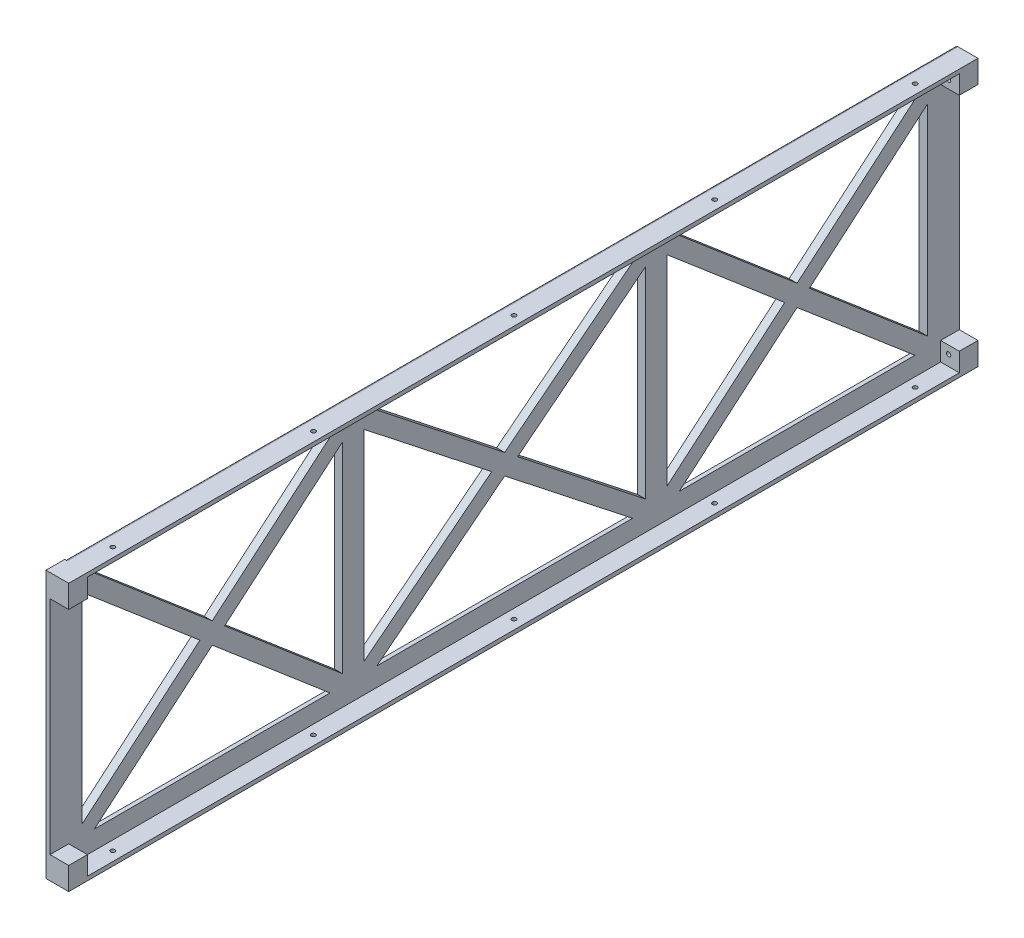
SolidWorks part; units mm, degrees
material "7075-T6 (SN)"
ref_plane "Front Plane" through (0, 0, 0) normal (0, 0, 1) x (1, 0, 0)
ref_plane "Top Plane" through (0, 0, 0) normal (0, 1, 0) x (1, 0, 0)
ref_plane "Right Plane" through (0, 0, 0) normal (1, 0, 0) x (0, 0, -1)
sketch "Sketch1" plane through (0, 0, 0) normal (0, 0, 1) x (1, 0, 0)
  line L0 (0, 0) -> (0, 100)
  line L1 (0, 100) -> (8.5, 100)
  line L2 (8.5, 100) -> (8.5, 98.5)
  line L3 (8.5, 98.5) -> (1.5, 98.5)
  line L4 (1.5, 98.5) -> (1.5, 1.5)
  line L5 (1.5, 1.5) -> (8.5, 1.5)
  line L6 (8.5, 1.5) -> (8.5, 0)
  line L7 (8.5, 0) -> (0, 0)
  dimension "D1" = 100
  dimension "D2" = 8.5
  dimension "D3" = 1.5
  dimension "D4" = 1.5
  dimension "D5" = 1.5
extrude "Profile" add sketch "Sketch1" along normal blind 340.5
ref_plane "Mid" through (0, 0, 170.25) normal (0, 0, 1) x (1, 0, 0)
sketch "Sketch2" plane through (0, 0, 0) normal (0, 0, 1) x (1, 0, 0)
  line L1 (0, 0) -> (8.5, 0)
  line L2 (0, 0) -> (0, 8.5)
  line L3 (0, 8.5) -> (8.5, 8.5)
  line L4 (8.5, 0) -> (8.5, 8.5)
  line L5 (0, 100) -> (8.5, 100)
  line L6 (0, 100) -> (0, 91.5)
  line L7 (0, 91.5) -> (8.5, 91.5)
  line L8 (8.5, 100) -> (8.5, 91.5)
  dimension "D1" = 8.5
  dimension "D2" = 8.5
  dimension "D3" = 8.5
  dimension "D4" = 8.5
extrude "Feet" add sketch "Sketch2" along normal blind 7
sketch "Sketch5" plane through (0, 0, 0) normal (1, 0, 0) x (0, 0, -1)
  line L0 (-340.5, 100) -> (0, 100) construction
  line L1 (-15, 91.5) -> (-106.5, 91.5)
  line L2 (-12, 88.5) -> (-12, 11.5)
  line L3 (-15, 8.5) -> (-106.5, 8.5)
  line L4 (-109.5, 88.5) -> (-109.5, 11.5)
  line L5 (-120.5, 91.5) -> (-220, 91.5)
  line L6 (-117.5, 88.5) -> (-117.5, 11.5)
  line L7 (-120.5, 8.5) -> (-220, 8.5)
  line L8 (-223, 88.5) -> (-223, 11.5)
  line L9 (-234, 91.5) -> (-325.5, 91.5)
  line L10 (-231, 88.5) -> (-231, 11.5)
  line L11 (-234, 8.5) -> (-325.5, 8.5)
  line L12 (-328.5, 88.5) -> (-328.5, 11.5)
  line L13 (0, 100) -> (0, 0) construction
  arc A0 (-325.5, 91.5) -> (-328.5, 88.5) centre (-325.5, 88.5) ccw
  arc A1 (-231, 11.5) -> (-234, 8.5) centre (-234, 11.5) cw
  arc A2 (-325.5, 8.5) -> (-328.5, 11.5) centre (-325.5, 11.5) cw
  arc A3 (-234, 91.5) -> (-231, 88.5) centre (-234, 88.5) cw
  arc A4 (-220, 91.5) -> (-223, 88.5) centre (-220, 88.5) ccw
  arc A5 (-117.5, 11.5) -> (-120.5, 8.5) centre (-120.5, 11.5) cw
  arc A6 (-220, 8.5) -> (-223, 11.5) centre (-220, 11.5) cw
  arc A7 (-120.5, 91.5) -> (-117.5, 88.5) centre (-120.5, 88.5) cw
  arc A8 (-106.5, 91.5) -> (-109.5, 88.5) centre (-106.5, 88.5) ccw
  arc A9 (-12, 11.5) -> (-15, 8.5) centre (-15, 11.5) cw
  arc A10 (-106.5, 8.5) -> (-109.5, 11.5) centre (-106.5, 11.5) cw
  arc A11 (-15, 91.5) -> (-12, 88.5) centre (-15, 88.5) cw
  point P18 (-328.5, 91.5)
  point P21 (-231, 8.5)
  point P26 (-231, 91.5)
  point P29 (-223, 91.5)
  point P36 (-117.5, 91.5)
  point P39 (-109.5, 91.5)
  point P46 (-12, 91.5)
  dimension "D2" = 3
  dimension "D1" = 97.5
  dimension "D4" = 83
  dimension "D5" = 105.5
  dimension "D6" = 97.5
  dimension "D7" = 8.5
  dimension "D8" = 12
  dimension "D9" = 8
  dimension "D10" = 8
extrude "Pockets" cut sketch "Sketch5" along normal through all
fillet "Rail Edge R1" radius 1 2 edges at (0, 0, 170.25) (0, 100, 170.25)
mirror "Feet Mirror" about plane through (0, 0, 170.25) normal (0, 0, 1) of "Feet"
ref_plane "MidWidth" through (0, 50, 0) normal (0, 1, 0) x (1, 0, 0)
sketch "M2 tap holes sketch" plane through (0, 0, 0) normal (0, -1, 0) x (1, 0, 0)
  circle A0 centre (5, 20) radius 0.8
  circle A1 centre (5, 95.125) radius 0.8
  circle A2 centre (5, 170.25) radius 0.8
  circle A3 centre (5, 245.375) radius 0.8
  circle A4 centre (5, 320.5) radius 0.8
extrude "M2 Tap Holes (1.6 drill)" cut sketch "M2 tap holes sketch" against normal through all
sketch "Foot taps sketch z0 end" plane through (0, 0, 7) normal (0, 0, 1) x (1, 0, 0)
  circle A0 centre (4.5, 5.5) radius 0.8
  circle A1 centre (4.5, 94.5) radius 0.8
extrude "M2 Foot Taps (1.6 drill, 5 deep) z0 end" cut sketch "Foot taps sketch z0 end" against normal blind 5
sketch "Foot taps sketch z340 end" plane through (0, 0, 333.5) normal (0, 0, -1) x (-1, 0, 0)
  circle A0 centre (-4.5, 5.5) radius 0.8
  circle A1 centre (-4.5, 94.5) radius 0.8
extrude "M2 Foot Taps (1.6 drill, 5 deep) z340 end" cut sketch "Foot taps sketch z340 end" against normal blind 5
sketch "Braces / sketch" plane through (0, 0, 0) normal (-1, 0, 0) x (0, 0, 1)
  line L0 (12, 8.5) -> (109.5, 91.5)
  line L1 (117.5, 8.5) -> (223, 91.5)
  line L2 (231, 8.5) -> (328.5, 91.5)
extrude "Braces /" add sketch "Braces / sketch" against normal blind 1.5 thin
sketch "Braces \\ sketch" plane through (0, 0, 0) normal (-1, 0, 0) x (0, 0, 1)
  line L0 (12, 91.5) -> (109.5, 8.5)
  line L1 (117.5, 91.5) -> (223, 8.5)
  line L2 (231, 91.5) -> (328.5, 8.5)
extrude "Braces \\" add sketch "Braces \\ sketch" against normal blind 1.5 thin
sketch "Braces / outer sketch" plane through (0, 0, 0) normal (-1, 0, 0) x (0, 0, 1)
  line L0 (12, 8.5) -> (109.5, 91.5)
  line L1 (117.5, 8.5) -> (223, 91.5)
  line L2 (231, 8.5) -> (328.5, 91.5)
extrude "Braces / outer" add sketch "Braces / outer sketch" along normal blind 1.5 thin
sketch "Braces \\ outer sketch" plane through (0, 0, 0) normal (-1, 0, 0) x (0, 0, 1)
  line L0 (12, 91.5) -> (109.5, 8.5)
  line L1 (117.5, 91.5) -> (223, 8.5)
  line L2 (231, 91.5) -> (328.5, 8.5)
extrude "Braces \\ outer" add sketch "Braces \\ outer sketch" along normal blind 1.5 thin
sketch "Panel pads sketch" plane through (0, 0, 0) normal (-1, 0, 0) x (0, 0, 1)
  line L1 (4, 8.5) -> (12, 8.5)
  line L2 (4, 8.5) -> (4, 91.5)
  line L3 (4, 91.5) -> (12, 91.5)
  line L4 (12, 8.5) -> (12, 91.5)
  line L6 (109.5, 8.5) -> (117.5, 8.5)
  line L7 (109.5, 8.5) -> (109.5, 91.5)
  line L8 (109.5, 91.5) -> (117.5, 91.5)
  line L9 (117.5, 8.5) -> (117.5, 91.5)
  line L11 (223, 8.5) -> (231, 8.5)
  line L12 (223, 8.5) -> (223, 91.5)
  line L13 (223, 91.5) -> (231, 91.5)
  line L14 (231, 8.5) -> (231, 91.5)
  line L16 (328.5, 8.5) -> (336.5, 8.5)
  line L17 (328.5, 8.5) -> (328.5, 91.5)
  line L18 (328.5, 91.5) -> (336.5, 91.5)
  line L19 (336.5, 8.5) -> (336.5, 91.5)
extrude "Panel pads" add sketch "Panel pads sketch" along normal blind 1.5
